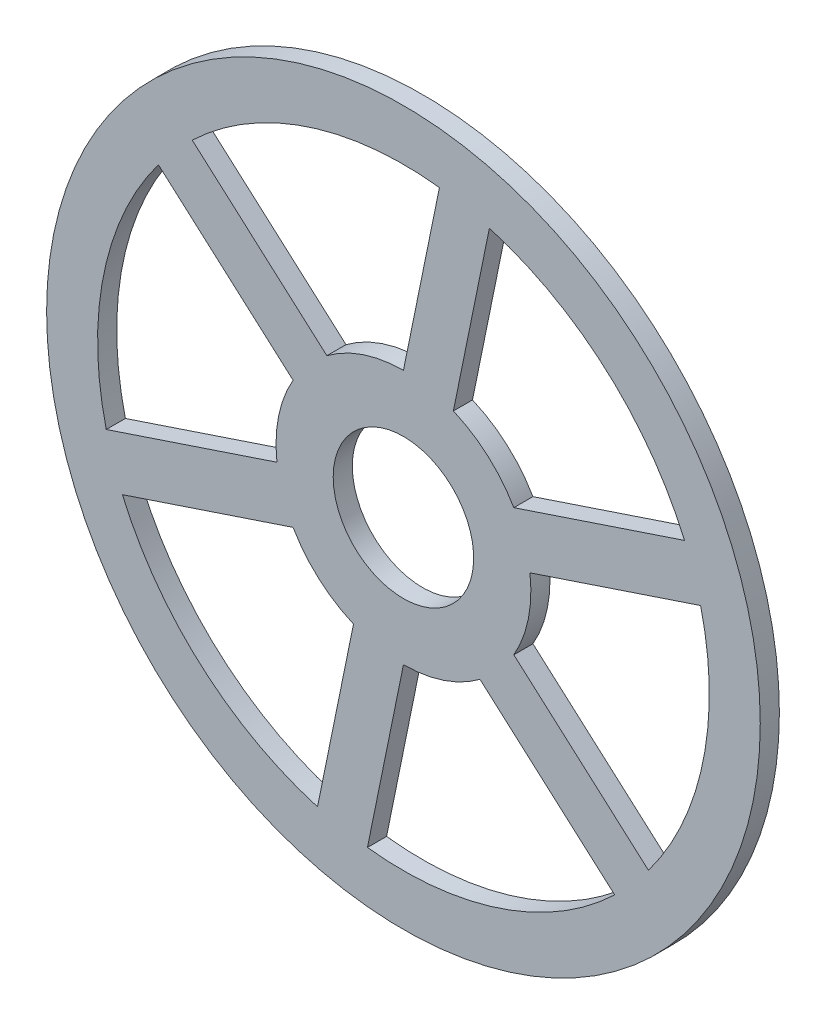
SolidWorks part; units mm, degrees
ref_plane "Front Plane" through (0, 0, 0) normal (0, 0, 1) x (1, 0, 0)
ref_plane "Top Plane" through (0, 0, 0) normal (0, 1, 0) x (1, 0, 0)
ref_plane "Right Plane" through (0, 0, 0) normal (1, 0, 0) x (0, 0, -1)
sketch "Sketch1" plane through (0, 0, 0) normal (0, 0, 1) x (1, 0, 0)
  line L0 (8.9653, 75.6708) -> (0, 31.75)
  line L3 (0, 0) -> (0, 31.75) construction
  line L4 (-52.6287, 55.1059) -> (-19.0749, 25.3813)
  line L6 (70.0154, 30.0712) -> (27.4963, 15.875)
  line L7 (21.4087, 73.1308) -> (12.4434, 29.21)
  line L8 (61.0502, -45.5995) -> (27.4963, -15.875)
  line L9 (74.0374, 18.0249) -> (31.5183, 3.8287)
  line L10 (-8.9653, -75.6708) -> (0, -31.75)
  line L11 (52.6287, -55.1059) -> (19.0749, -25.3813)
  line L12 (-70.0154, -30.0712) -> (-27.4963, -15.875)
  line L13 (-21.4087, -73.1308) -> (-12.4434, -29.21)
  line L15 (-61.0502, 45.5995) -> (-27.4963, 15.875)
  line L16 (21.4087, 73.1308) -> (8.9653, 75.6708) construction
  line L17 (12.1485, 29.1922) -> (12.4434, 29.21) construction
  line L18 (12.4434, 29.21) -> (0, 31.75) construction
  line L20 (-74.0374, -18.0249) -> (-31.5183, -3.8287)
  circle A0 centre (0, 0) radius 17.5
  circle A3 centre (0, 0) radius 88.9
  arc A5 (-19.0749, 25.3813) -> (0, 31.75) centre (0, 0) cw
  arc A6 (-52.6287, 55.1059) -> (8.9653, 75.6708) centre (0, 0) cw
  arc A7 (21.4087, 73.1308) -> (70.0154, 30.0712) centre (0, 0) cw
  arc A8 (12.4434, 29.21) -> (27.4963, 15.875) centre (0, 0) cw
  arc A10 (74.0374, 18.0249) -> (61.0502, -45.5995) centre (0, 0) cw
  arc A11 (31.5183, 3.8287) -> (27.4963, -15.875) centre (0, 0) cw
  arc A12 (52.6287, -55.1059) -> (-8.9653, -75.6708) centre (0, 0) cw
  arc A14 (19.0749, -25.3813) -> (0, -31.75) centre (0, 0) cw
  arc A15 (-21.4087, -73.1308) -> (-70.0154, -30.0712) centre (0, 0) cw
  arc A16 (-12.4434, -29.21) -> (-27.4963, -15.875) centre (0, 0) cw
  arc A17 (-74.0374, -18.0249) -> (-61.0502, 45.5995) centre (0, 0) cw
  arc A18 (-31.5183, -3.8287) -> (-27.4963, 15.875) centre (0, 0) cw
  point P31 (0, 0)
  dimension "D1" = 35
  dimension "D2" = 177.8
  dimension "D3" = 31.75
  dimension "D4" = 76.2
  dimension "D5" = 12.7
  dimension "D6" = 6
  dimension "D7" = 6
extrude "Boss-Extrude1" add sketch "Sketch1" along normal blind 4.7625
